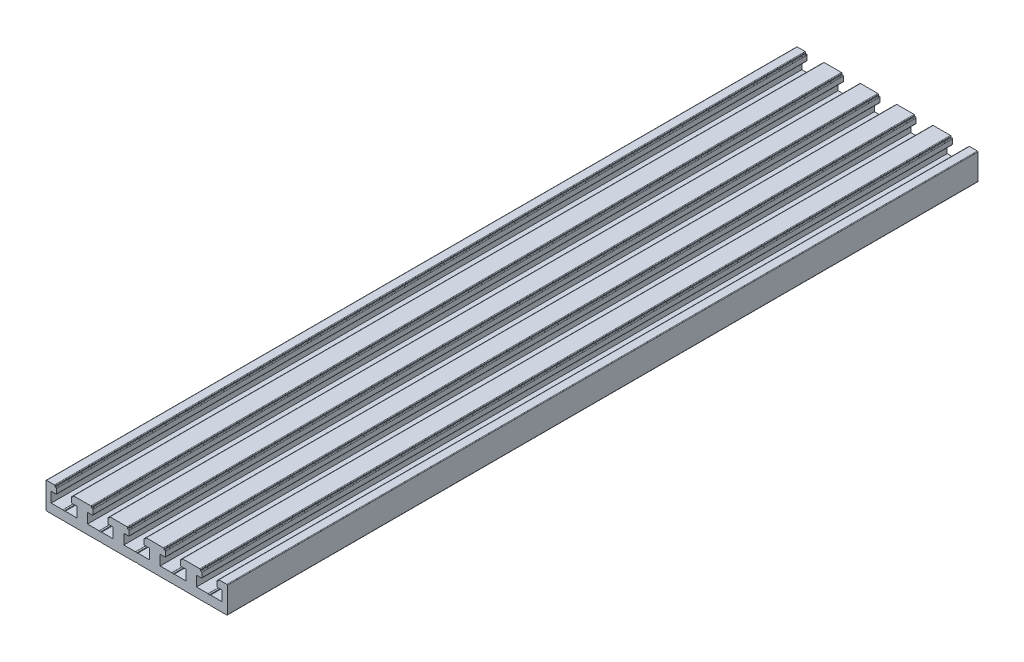
SolidWorks part; units mm, degrees
material "6061-T6 (SS)"
ref_plane "Front Plane" through (0, 0, 0) normal (0, 0, 1) x (1, 0, 0)
ref_plane "Top Plane" through (0, 0, 0) normal (0, 1, 0) x (1, 0, 0)
ref_plane "Right Plane" through (0, 0, 0) normal (1, 0, 0) x (0, 0, -1)
sketch "Sketch1" plane through (0, 0, 0) normal (0, 0, -1) x (-1, 0, 0)
  line L0 (0, 1.72) -> (0, -1.72) construction
  line L1 (-37.45, 8.85) -> (-37.45, -1.65)
  line L2 (-37.2, -1.9) -> (-30.5436, -1.9)
  line L3 (-30.4589, -1.8852) -> (-30, -1.72)
  line L4 (-30, -1.72) -> (-29.5411, -1.8852)
  line L5 (-29.4564, -1.9) -> (-15.5436, -1.9)
  line L6 (-15.4589, -1.8852) -> (-15, -1.72)
  line L7 (-15, -1.72) -> (-14.5411, -1.8852)
  line L8 (-14.4564, -1.9) -> (-0.5436, -1.9)
  line L9 (-0.4589, -1.8852) -> (0, -1.72)
  line L10 (0, -1.72) -> (0.4589, -1.8852)
  line L11 (0.5436, -1.9) -> (14.4564, -1.9)
  line L12 (14.5411, -1.8852) -> (15, -1.72)
  line L13 (15, -1.72) -> (15.4589, -1.8852)
  line L14 (15.5436, -1.9) -> (29.4564, -1.9)
  line L15 (29.5411, -1.8852) -> (30, -1.72)
  line L16 (30, -1.72) -> (30.4589, -1.8852)
  line L17 (30.5436, -1.9) -> (37.2, -1.9)
  line L18 (37.45, -1.65) -> (37.45, 8.85)
  line L19 (37.2, 9.1) -> (33.95, 9.1)
  line L20 (33.7, 8.85) -> (33.7, 8.5)
  line L21 (33.7, 8.5) -> (33.32, 8.5)
  line L22 (33.07, 8.25) -> (33.07, 6.35)
  line L23 (33.32, 6.1) -> (35.3, 6.1)
  line L24 (35.3, 6.1) -> (35.3, 1.9)
  line L25 (35.3, 1.9) -> (30.5436, 1.9)
  line L26 (30.4589, 1.8852) -> (30, 1.72)
  line L27 (30, 1.72) -> (29.5411, 1.8852)
  line L28 (29.4564, 1.9) -> (24.7, 1.9)
  line L29 (24.7, 1.9) -> (24.7, 6.1)
  line L30 (24.7, 6.1) -> (26.68, 6.1)
  line L31 (26.93, 6.35) -> (26.93, 8.25)
  line L32 (26.68, 8.5) -> (26.3, 8.5)
  line L33 (26.3, 8.5) -> (26.3, 8.85)
  line L34 (26.05, 9.1) -> (18.95, 9.1)
  line L35 (18.7, 8.85) -> (18.7, 8.5)
  line L36 (18.7, 8.5) -> (18.32, 8.5)
  line L37 (18.07, 8.25) -> (18.07, 6.35)
  line L38 (18.32, 6.1) -> (20.3, 6.1)
  line L39 (20.3, 6.1) -> (20.3, 1.9)
  line L40 (20.3, 1.9) -> (15.5436, 1.9)
  line L41 (15.4589, 1.8852) -> (15, 1.72)
  line L42 (15, 1.72) -> (14.5411, 1.8852)
  line L43 (14.4564, 1.9) -> (9.7, 1.9)
  line L44 (9.7, 1.9) -> (9.7, 6.1)
  line L45 (9.7, 6.1) -> (11.68, 6.1)
  line L46 (11.93, 6.35) -> (11.93, 8.25)
  line L47 (11.68, 8.5) -> (11.3, 8.5)
  line L48 (11.3, 8.5) -> (11.3, 8.85)
  line L49 (11.05, 9.1) -> (3.95, 9.1)
  line L50 (3.7, 8.85) -> (3.7, 8.5)
  line L51 (3.7, 8.5) -> (3.32, 8.5)
  line L52 (3.07, 8.25) -> (3.07, 6.35)
  line L53 (3.32, 6.1) -> (5.3, 6.1)
  line L54 (5.3, 6.1) -> (5.3, 1.9)
  line L55 (5.3, 1.9) -> (0.5436, 1.9)
  line L56 (0.4589, 1.8852) -> (0, 1.72)
  line L57 (0, 1.72) -> (-0.4589, 1.8852)
  line L58 (-0.5436, 1.9) -> (-5.3, 1.9)
  line L59 (-5.3, 1.9) -> (-5.3, 6.1)
  line L60 (-5.3, 6.1) -> (-3.32, 6.1)
  line L61 (-3.07, 6.35) -> (-3.07, 8.25)
  line L62 (-3.32, 8.5) -> (-3.7, 8.5)
  line L63 (-3.7, 8.5) -> (-3.7, 8.85)
  line L64 (-3.95, 9.1) -> (-11.05, 9.1)
  line L65 (-11.3, 8.85) -> (-11.3, 8.5)
  line L66 (-11.3, 8.5) -> (-11.68, 8.5)
  line L67 (-11.93, 8.25) -> (-11.93, 6.35)
  line L68 (-11.68, 6.1) -> (-9.7, 6.1)
  line L69 (-9.7, 6.1) -> (-9.7, 1.9)
  line L70 (-9.7, 1.9) -> (-14.4564, 1.9)
  line L71 (-14.5411, 1.8852) -> (-15, 1.72)
  line L72 (-15, 1.72) -> (-15.4589, 1.8852)
  line L73 (-15.5436, 1.9) -> (-20.3, 1.9)
  line L74 (-20.3, 1.9) -> (-20.3, 6.1)
  line L75 (-20.3, 6.1) -> (-18.32, 6.1)
  line L76 (-18.07, 6.35) -> (-18.07, 8.25)
  line L77 (-18.32, 8.5) -> (-18.7, 8.5)
  line L78 (-18.7, 8.5) -> (-18.7, 8.85)
  line L79 (-18.95, 9.1) -> (-26.05, 9.1)
  line L80 (-26.3, 8.85) -> (-26.3, 8.5)
  line L81 (-26.3, 8.5) -> (-26.68, 8.5)
  line L82 (-26.93, 8.25) -> (-26.93, 6.35)
  line L83 (-26.68, 6.1) -> (-24.7, 6.1)
  line L84 (-24.7, 6.1) -> (-24.7, 1.9)
  line L85 (-24.7, 1.9) -> (-29.4564, 1.9)
  line L86 (-29.5411, 1.8852) -> (-30, 1.72)
  line L87 (-30, 1.72) -> (-30.4589, 1.8852)
  line L88 (-30.5436, 1.9) -> (-35.3, 1.9)
  line L89 (-35.3, 1.9) -> (-35.3, 6.1)
  line L90 (-35.3, 6.1) -> (-33.32, 6.1)
  line L91 (-33.07, 6.35) -> (-33.07, 8.25)
  line L92 (-33.32, 8.5) -> (-33.7, 8.5)
  line L93 (-33.7, 8.5) -> (-33.7, 8.85)
  line L94 (-33.95, 9.1) -> (-37.2, 9.1)
  arc A0 (-37.45, -1.65) -> (-37.2, -1.9) centre (-37.2, -1.65) ccw
  arc A1 (-30.5436, -1.9) -> (-30.4589, -1.8852) centre (-30.5436, -1.65) ccw
  arc A2 (-29.5411, -1.8852) -> (-29.4564, -1.9) centre (-29.4564, -1.65) ccw
  arc A3 (-15.5436, -1.9) -> (-15.4589, -1.8852) centre (-15.5436, -1.65) ccw
  arc A4 (-14.5411, -1.8852) -> (-14.4564, -1.9) centre (-14.4564, -1.65) ccw
  arc A5 (-0.5436, -1.9) -> (-0.4589, -1.8852) centre (-0.5436, -1.65) ccw
  arc A6 (0.4589, -1.8852) -> (0.5436, -1.9) centre (0.5436, -1.65) ccw
  arc A7 (14.4564, -1.9) -> (14.5411, -1.8852) centre (14.4564, -1.65) ccw
  arc A8 (15.4589, -1.8852) -> (15.5436, -1.9) centre (15.5436, -1.65) ccw
  arc A9 (29.4564, -1.9) -> (29.5411, -1.8852) centre (29.4564, -1.65) ccw
  arc A10 (30.4589, -1.8852) -> (30.5436, -1.9) centre (30.5436, -1.65) ccw
  arc A11 (37.2, -1.9) -> (37.45, -1.65) centre (37.2, -1.65) ccw
  arc A12 (37.45, 8.85) -> (37.2, 9.1) centre (37.2, 8.85) ccw
  arc A13 (33.95, 9.1) -> (33.7, 8.85) centre (33.95, 8.85) ccw
  arc A14 (33.32, 8.5) -> (33.07, 8.25) centre (33.32, 8.25) ccw
  arc A15 (33.07, 6.35) -> (33.32, 6.1) centre (33.32, 6.35) ccw
  arc A16 (30.5436, 1.9) -> (30.4589, 1.8852) centre (30.5436, 1.65) ccw
  arc A17 (29.5411, 1.8852) -> (29.4564, 1.9) centre (29.4564, 1.65) ccw
  arc A18 (26.68, 6.1) -> (26.93, 6.35) centre (26.68, 6.35) ccw
  arc A19 (26.93, 8.25) -> (26.68, 8.5) centre (26.68, 8.25) ccw
  arc A20 (26.3, 8.85) -> (26.05, 9.1) centre (26.05, 8.85) ccw
  arc A21 (18.95, 9.1) -> (18.7, 8.85) centre (18.95, 8.85) ccw
  arc A22 (18.32, 8.5) -> (18.07, 8.25) centre (18.32, 8.25) ccw
  arc A23 (18.07, 6.35) -> (18.32, 6.1) centre (18.32, 6.35) ccw
  arc A24 (15.5436, 1.9) -> (15.4589, 1.8852) centre (15.5436, 1.65) ccw
  arc A25 (14.5411, 1.8852) -> (14.4564, 1.9) centre (14.4564, 1.65) ccw
  arc A26 (11.68, 6.1) -> (11.93, 6.35) centre (11.68, 6.35) ccw
  arc A27 (11.93, 8.25) -> (11.68, 8.5) centre (11.68, 8.25) ccw
  arc A28 (11.3, 8.85) -> (11.05, 9.1) centre (11.05, 8.85) ccw
  arc A29 (3.95, 9.1) -> (3.7, 8.85) centre (3.95, 8.85) ccw
  arc A30 (3.32, 8.5) -> (3.07, 8.25) centre (3.32, 8.25) ccw
  arc A31 (3.07, 6.35) -> (3.32, 6.1) centre (3.32, 6.35) ccw
  arc A32 (0.5436, 1.9) -> (0.4589, 1.8852) centre (0.5436, 1.65) ccw
  arc A33 (-0.4589, 1.8852) -> (-0.5436, 1.9) centre (-0.5436, 1.65) ccw
  arc A34 (-3.32, 6.1) -> (-3.07, 6.35) centre (-3.32, 6.35) ccw
  arc A35 (-3.07, 8.25) -> (-3.32, 8.5) centre (-3.32, 8.25) ccw
  arc A36 (-3.7, 8.85) -> (-3.95, 9.1) centre (-3.95, 8.85) ccw
  arc A37 (-11.05, 9.1) -> (-11.3, 8.85) centre (-11.05, 8.85) ccw
  arc A38 (-11.68, 8.5) -> (-11.93, 8.25) centre (-11.68, 8.25) ccw
  arc A39 (-11.93, 6.35) -> (-11.68, 6.1) centre (-11.68, 6.35) ccw
  arc A40 (-14.4564, 1.9) -> (-14.5411, 1.8852) centre (-14.4564, 1.65) ccw
  arc A41 (-15.4589, 1.8852) -> (-15.5436, 1.9) centre (-15.5436, 1.65) ccw
  arc A42 (-18.32, 6.1) -> (-18.07, 6.35) centre (-18.32, 6.35) ccw
  arc A43 (-18.07, 8.25) -> (-18.32, 8.5) centre (-18.32, 8.25) ccw
  arc A44 (-18.7, 8.85) -> (-18.95, 9.1) centre (-18.95, 8.85) ccw
  arc A45 (-26.05, 9.1) -> (-26.3, 8.85) centre (-26.05, 8.85) ccw
  arc A46 (-26.68, 8.5) -> (-26.93, 8.25) centre (-26.68, 8.25) ccw
  arc A47 (-26.93, 6.35) -> (-26.68, 6.1) centre (-26.68, 6.35) ccw
  arc A48 (-29.4564, 1.9) -> (-29.5411, 1.8852) centre (-29.4564, 1.65) ccw
  arc A49 (-30.4589, 1.8852) -> (-30.5436, 1.9) centre (-30.5436, 1.65) ccw
  arc A50 (-33.32, 6.1) -> (-33.07, 6.35) centre (-33.32, 6.35) ccw
  arc A51 (-33.07, 8.25) -> (-33.32, 8.5) centre (-33.32, 8.25) ccw
  arc A52 (-33.7, 8.85) -> (-33.95, 9.1) centre (-33.95, 8.85) ccw
  arc A53 (-37.2, 9.1) -> (-37.45, 8.85) centre (-37.2, 8.85) ccw
  point P2 (0, 0)
  dimension "D1" = 11
  dimension "D2" = 74.9
extrude "Base" add sketch "Sketch1" against normal blind 310
hole_wizard "CSK for M3 Flat Head Machine Screw1" positions "3DSketch1" profile "Sketch2" countersink size "M3" standard "ANSI Metric" end condition through all
sketch3d "3DSketch1"
  point P0 (-30, 1.9, 65)
  point P2 (30, 1.9, 65)
  point P35 (30, 1.9, 279.9999)
  point P37 (-30, 1.9, 279.9999)
  dimension "D1" = 65
  dimension "D2" = 7.45
  dimension "D3" = 60
  dimension "D4" = 280
sketch "Sketch2" plane through (-30, 1.9, 65) normal (1, 0, 0) x (0, 0, 1)
  line L0 (0, 0) -> (0, 3.8)
  line L1 (0, 3.8) -> (1.6, 3.8)
  line L2 (1.6, 3.8) -> (1.6, 1.4)
  line L3 (1.6, 1.4) -> (3, 0)
  line L5 (3, 0) -> (0, 0)
  line L6 (-1.6, 1.4) -> (-3, 0) construction
  line L11 (0, -6.35) -> (0, 107.95) construction
  dimension "Thru Hole Dia." = 3.2
  dimension "Thru Hole Depth" = 3.8
  dimension "Near C'Sink Dia." = 6
  dimension "Near C'Sink Angle" = 90
hole_wizard "M4x0.7 Tapped Hole1" positions "Sketch4" profile "Sketch5" tap size "M4x0.7" standard "ANSI Metric" end condition through all
sketch "Sketch4" plane through (0, 1.9, 0) normal (0, 1, 0) x (1, 0, 0)
  line L1 (-0.5436, 0) -> (-14.4564, 0) construction
  line L2 (-37.45, -310) -> (-37.45, 0) construction
  point P0 (15, -30)
  dimension "D1" = 30
  dimension "D2" = 52.45
sketch "Sketch5" plane through (15, 1.9, 30) normal (1, 0, 0) x (0, 0, 1)
  line L0 (0, 0) -> (0, 3.8)
  line L1 (0, 3.8) -> (1.65, 3.8)
  line L2 (1.65, 3.8) -> (1.65, 0)
  line L5 (1.65, 0) -> (0, 0)
  line L11 (0, -6.35) -> (0, 107.95) construction
  dimension "Thru Tap Drill Dia." = 3.3
  dimension "Thru Tap Drill Depth" = 3.8
cosmetic thread "Hole Thread3" parameters "D2"=4
sketch "Sketch6" [suppressed] plane through (0, 0, 0) normal (0, 0, -1) x (-1, 0, 0)
  line L1 (-14.5411, -9.9057) -> (-41.3903, -9.9057)
  line L2 (-14.5411, -9.9057) -> (-14.5411, 14.5956)
  line L3 (-14.5411, 14.5956) -> (-41.3903, 14.5956)
  line L4 (-41.3903, -9.9057) -> (-41.3903, 14.5956)
extrude "Cut-Extrude1" [suppressed] cut sketch "Sketch6" against normal through all
